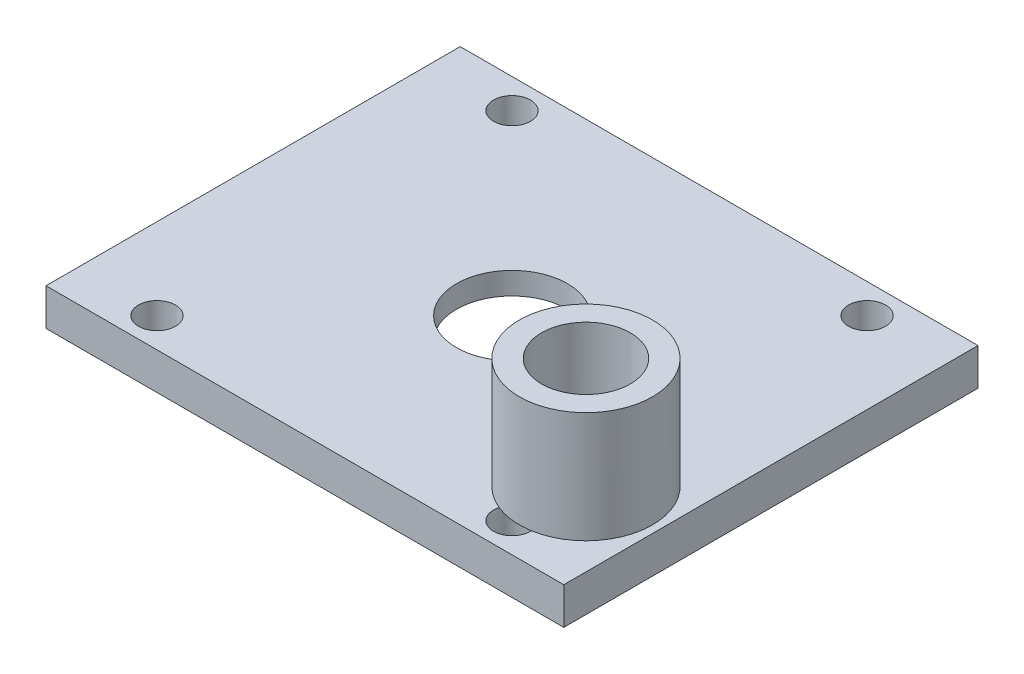
SolidWorks part; units mm, degrees
ref_plane "Front Plane" through (0, 0, 0) normal (0, 0, 1) x (1, 0, 0)
ref_plane "Top Plane" through (0, 0, 0) normal (0, 1, 0) x (1, 0, 0)
ref_plane "Right Plane" through (0, 0, 0) normal (1, 0, 0) x (0, 0, -1)
sketch "Sketch1" plane through (0, 0, 0) normal (0, 1, 0) x (1, 0, 0)
  line L1 (-35, -28) -> (35, -28)
  line L2 (-35, -28) -> (-35, 28)
  line L3 (-35, 28) -> (35, 28)
  line L4 (35, -28) -> (35, 28)
  line L5 (-35, -28) -> (35, 28) construction
  line L6 (-35, 28) -> (35, -28) construction
  point P0 (0, 0)
  dimension "D1" = 70
  dimension "D2" = 56
extrude "Boss-Extrude1" add sketch "Sketch1" along normal blind 5
sketch "Sketch2" plane through (0, 5, 0) normal (0, 1, 0) x (1, 0, 0)
  circle A0 centre (25, -15) radius 9
  point P2 (0, 0)
  dimension "D1" = 18
  dimension "D2" = 15
  dimension "D3" = 25
extrude "Boss-Extrude2" add sketch "Sketch2" along normal blind 15
sketch "Sketch4" plane through (0, 0, 0) normal (0, -1, 0) x (1, 0, 0)
  circle A0 centre (0, 0) radius 19
  dimension "D1" = 38
extrude "Cut-Extrude2" cut sketch "Sketch4" against normal blind 2
sketch "Sketch5" plane through (0, 2, 0) normal (0, -1, 0) x (1, 0, 0)
  circle A0 centre (0, 0) radius 7.5
  dimension "D1" = 15
extrude "Cut-Extrude3" cut sketch "Sketch5" against normal through all and the other way through all
sketch "Sketch6" plane through (0, 20, 0) normal (0, 1, 0) x (1, 0, 0)
  circle A0 centre (25, -15) radius 6
  dimension "D1" = 12
extrude "Cut-Extrude4" cut sketch "Sketch6" along direction (0, -1, 0) on the side against the normal up to surface (15 mm away)
sketch "Sketch7" plane through (0, 5, 0) normal (0, 1, 0) x (1, 0, 0)
  circle A0 centre (-24, 24) radius 2.5
  circle A1 centre (24, 24) radius 2.5
  circle A2 centre (24, -24) radius 2.5
  circle A3 centre (-24, -24) radius 2.5
  point P2 (0, 0)
  point P13 (0, 0)
  dimension "D1" = 24
  dimension "D2" = 5
  dimension "D3" = 24
  dimension "D4" = 4
extrude "Cut-Extrude5" cut sketch "Sketch7" against normal through all
